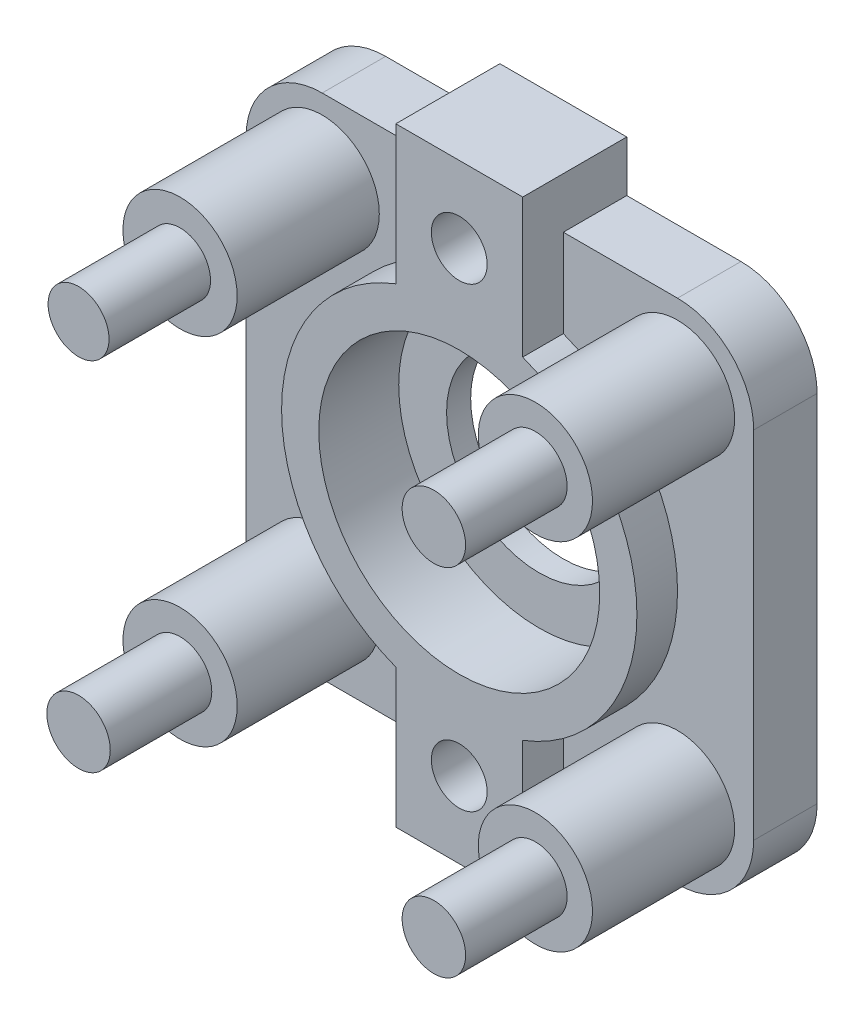
SolidWorks part; units mm, degrees
ref_plane "前视基准面" through (0, 0, 0) normal (0, 0, 1) x (1, 0, 0)
ref_plane "上视基准面" through (0, 0, 0) normal (0, 1, 0) x (1, 0, 0)
ref_plane "右视基准面" through (0, 0, 0) normal (1, 0, 0) x (0, 0, -1)
sketch "草图1" plane through (0, 0, 0) normal (0, 0, 1) x (1, 0, 0)
  line L1 (-7, -10) -> (7, -10)
  line L2 (-10, -7) -> (-10, 7)
  line L3 (-7, 10) -> (7, 10)
  line L4 (10, -7) -> (10, 7)
  line L5 (-10, -10) -> (10, 10) construction
  line L6 (-10, 10) -> (10, -10) construction
  arc A0 (7, -10) -> (10, -7) centre (7, -7) ccw
  arc A1 (-10, 7) -> (-7, 10) centre (-7, 7) cw
  arc A2 (-7, -10) -> (-10, -7) centre (-7, -7) cw
  arc A3 (7, 10) -> (10, 7) centre (7, 7) cw
  point P0 (0, 0)
  dimension "D2" = 3
  dimension "D1" = 20
extrude "凸台-拉伸1" add sketch "草图1" along normal blind 1.5
sketch "草图4" plane through (0, 0, 1.5) normal (0, 0, 1) x (1, 0, 0)
  circle A0 centre (-7, -7) radius 2.25
  circle A1 centre (7, -7) radius 2.25
  circle A2 centre (7, 7) radius 2.25
  circle A3 centre (-7, 7) radius 2.25
  dimension "D1" = 4.5
  dimension "D2" = 4.5
  dimension "D3" = 4.5
  dimension "D4" = 4.5
extrude "凸台-拉伸2" add sketch "草图4" along normal blind 6.6
sketch "草图5" plane through (0, 0, 8.1) normal (0, 0, 1) x (1, 0, 0)
  circle A0 centre (-7, 7) radius 1.2
  circle A1 centre (-7, -7) radius 1.25
  circle A2 centre (7, -7) radius 1.25
  circle A3 centre (7, 7) radius 1.25
  dimension "D1" = 2.4
  dimension "D2" = 2.5
  dimension "D3" = 2.5
  dimension "D4" = 2.5
extrude "凸台-拉伸3" add sketch "草图5" along normal blind 4
sketch "草图6" plane through (0, 0, 1.5) normal (0, 0, 1) x (1, 0, 0)
  circle A0 centre (0, 0) radius 7
  dimension "D1" = 14
extrude "凸台-拉伸4" add sketch "草图6" along normal blind 2.6
sketch "草图7" plane through (0, 0, 4.1) normal (0, 0, 1) x (1, 0, 0)
  circle A0 centre (0, 0) radius 5.535
  dimension "D1" = 11.07
extrude "切除-拉伸1" cut sketch "草图7" against normal blind 3.15
sketch "草图8" plane through (0, 0, 0.95) normal (0, 0, 1) x (1, 0, 0)
  circle A0 centre (0, 0) radius 3.65
  dimension "D1" = 7.3
extrude "切除-拉伸2" cut sketch "草图8" against normal blind 5.65
sketch "草图11" plane through (0, 0, 4.1) normal (0, 0, 1) x (1, 0, 0)
  line L0 (0, 0) -> (0, 9.0015) construction
  line L1 (7, 10) -> (-7, 10) construction
  line L2 (-2.5, 12) -> (2.5, 12)
  line L3 (-2.5, 12) -> (-2.5, 6.0029)
  line L4 (-2.5, 6.0029) -> (2.5, 6.0029)
  line L5 (2.5, 12) -> (2.5, 6.0029)
  line L6 (-2.5, 12) -> (2.5, 6.0029) construction
  line L7 (-2.5, 6.0029) -> (2.5, 12) construction
  dimension "D1" = 5
  dimension "D2" = 2
extrude "凸台-拉伸6" add sketch "草图11" against normal up to surface (4.1 mm away) up to face at (3.65, 0, 0)
sketch "草图12" plane through (0, 0, 0) normal (0, 0, -1) x (-1, 0, 0)
  line L0 (0, 12) -> (0, 9) construction
  line L1 (2.5, 12) -> (-2.5, 12) construction
  circle A0 centre (0, 9) radius 2.1
  dimension "D2" = 4.2
  dimension "D1" = 3
extrude "切除-拉伸5" cut sketch "草图12" against normal blind 1.2
mirror "镜向1" about plane through (0, 0, 0) normal (0, 1, 0) of "切除-拉伸5", "凸台-拉伸6"
sketch "草图13" plane through (0, 0, 1.2) normal (0, 0, -1) x (-1, 0, 0)
  circle A0 centre (0, 9) radius 1.1
  circle A1 centre (0, -9) radius 1.1
  dimension "D1" = 2.2
  dimension "D2" = 2.2
extrude "切除-拉伸6" cut sketch "草图13" against normal blind 26.5
sketch "草图14" plane through (0, 0, 1.5) normal (0, 0, 1) x (1, 0, 0)
  line L5 (-7, -10) -> (-2.5, -10)
  line L6 (-2.5, -10) -> (-2.5, -6.5383)
  line L7 (-2.5, 6.5383) -> (-2.5, 10)
  line L8 (-2.5, 10) -> (-7, 10)
  line L9 (-10, 7) -> (-10, -7)
  line L10 (-7, -10) -> (-2.5, -10)
  line L11 (-2.5, -10) -> (-2.5, -6.5383)
  line L12 (-2.5, 6.5383) -> (-2.5, 10)
  line L13 (-2.5, 10) -> (-7, 10)
  line L14 (-10, 7) -> (-10, -7)
  line L15 (2.5, -6.5383) -> (2.5, -10)
  line L16 (2.5, -10) -> (7, -10)
  line L17 (10, -7) -> (10, 7)
  line L18 (7, 10) -> (2.5, 10)
  line L19 (2.5, 10) -> (2.5, 6.5383)
  line L20 (2.5, -6.5383) -> (2.5, -10)
  line L21 (2.5, -10) -> (7, -10)
  line L22 (10, -7) -> (10, 7)
  line L23 (7, 10) -> (2.5, 10)
  line L24 (2.5, 10) -> (2.5, 6.5383)
  arc A3 (-2.5, 6.5383) -> (-2.5, -6.5383) centre (0, 0) ccw
  arc A4 (-7, 10) -> (-10, 7) centre (-7, 7) ccw
  arc A5 (-10, -7) -> (-7, -10) centre (-7, -7) ccw
  arc A6 (-2.5, 6.5383) -> (-2.5, -6.5383) centre (0, 0) ccw
  arc A7 (-7, 10) -> (-10, 7) centre (-7, 7) ccw
  arc A8 (-10, -7) -> (-7, -10) centre (-7, -7) ccw
  arc A9 (2.5, -6.5383) -> (2.5, 6.5383) centre (0, 0) ccw
  arc A10 (7, -10) -> (10, -7) centre (7, -7) ccw
  arc A11 (10, 7) -> (7, 10) centre (7, 7) ccw
  arc A12 (2.5, -6.5383) -> (2.5, 6.5383) centre (0, 0) ccw
  arc A13 (7, -10) -> (10, -7) centre (7, -7) ccw
  arc A14 (10, 7) -> (7, 10) centre (7, 7) ccw
  dimension "D1" = 0
  dimension "D2" = 0
extrude "凸台-拉伸7" add sketch "草图14" along normal blind 1
